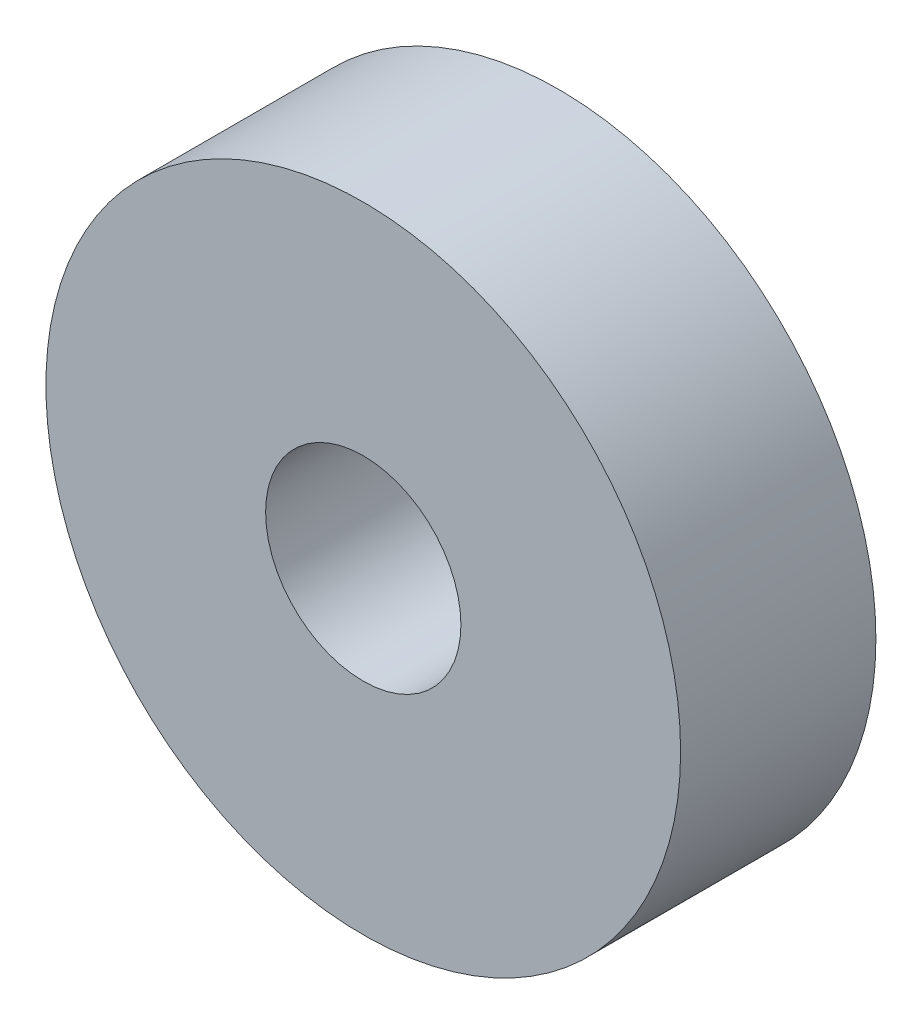
SolidWorks part; units mm, degrees
ref_plane "Ebene vorne" through (0, 0, 0) normal (0, 0, 1) x (1, 0, 0)
ref_plane "Ebene oben" through (0, 0, 0) normal (0, 1, 0) x (1, 0, 0)
ref_plane "Ebene rechts" through (0, 0, 0) normal (1, 0, 0) x (0, 0, -1)
sketch "Sketch1" plane through (0, 0, 0) normal (0, 0, 1) x (1, 0, 0)
  circle A0 centre (0, 0) radius 6.5
  circle A1 centre (0, 0) radius 2
  dimension "D1" = 13
  dimension "D2" = 4
extrude "Boss-Extrude1" add sketch "Sketch1" along normal blind 4
